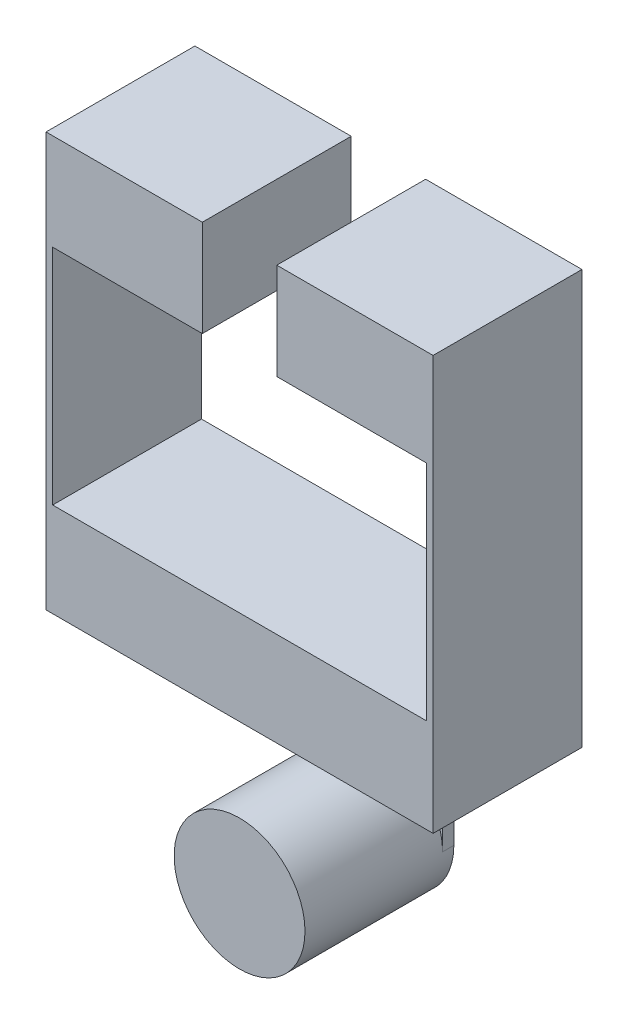
SolidWorks part; units mm, degrees
other "Markup1"
sketch "Sketch7" plane through (31.7043, 97.4003, 0) normal (0.5774, 0.5773, 0.5774) x (0.7071, 0, -0.7071)
ref_plane "Front Plane" through (0, 0, 0) normal (0, 0, 1) x (1, 0, 0)
ref_plane "Top Plane" through (0, 0, 0) normal (0, 1, 0) x (1, 0, 0)
ref_plane "Right Plane" through (0, 0, 0) normal (1, 0, 0) x (0, 0, -1)
sketch "Sketch1" plane through (0, 0, 0) normal (0, 0, 1) x (1, 0, 0)
  circle A0 centre (0, 0) radius 11.1628
  dimension "D1" = 22.3256
extrude "Boss-Extrude1" add sketch "Sketch1" against normal blind 25.4
sketch "Sketch2" plane through (0, 0, -25.4) normal (0, 0, -1) x (-1, 0, 0)
  line L0 (-11.1628, 0) -> (-11.1628, 25.4)
  line L1 (-11.1628, 25.4) -> (11.1628, 25.4)
  line L2 (11.1628, 25.4) -> (11.1628, 0)
  circle A0 centre (0, 0) radius 11.1628 construction
  arc A1 (11.1628, 0) -> (-11.1628, 0) centre (0, 0) ccw
  point P4 (0, 0)
  dimension "D1" = 22.3256
  dimension "D2" = 25.4
extrude "Boss-Extrude2" add sketch "Sketch2" against normal blind 1.9264
ref_plane "Plane1" through (0, 25.4, 0) normal (0, 1, 0) x (1, 0, 0)
sketch "Sketch4" plane through (0, 25.4, 0) normal (0, 1, 0) x (1, 0, 0)
  line L0 (0, 0) -> (0, 55.2267) construction
  line L1 (-33.02, 0) -> (33.02, 0)
  line L2 (-33.02, 0) -> (-33.02, 25.4)
  line L3 (-33.02, 25.4) -> (33.02, 25.4)
  line L4 (33.02, 0) -> (33.02, 25.4)
  point P6 (0, 0)
  dimension "D1" = 25.4
  dimension "D2" = 66.04
extrude "Boss-Extrude3" add sketch "Sketch4" along normal blind 16.0644
sketch "Sketch5" plane through (0, 41.4644, 0) normal (0, 1, 0) x (1, 0, 0)
  line L0 (-33.02, 0) -> (33.02, 0) construction
  line L1 (-33.02, 25.4) -> (-31.8904, 25.4)
  line L2 (-33.02, 25.4) -> (-33.02, 0)
  line L3 (-33.02, 0) -> (-31.8904, 0)
  line L4 (-31.8904, 25.4) -> (-31.8904, 0)
  line L6 (33.02, 25.4) -> (31.8904, 25.4)
  line L7 (33.02, 25.4) -> (33.02, 0)
  line L8 (33.02, 0) -> (31.8904, 0)
  line L9 (31.8904, 25.4) -> (31.8904, 0)
  dimension "D1" = 1.1296
  dimension "D2" = 1.1296
extrude "Boss-Extrude4" add sketch "Sketch5" along normal blind 38.1
sketch "Sketch6" plane through (0, 79.5644, 0) normal (0, 1, 0) x (1, 0, 0)
  line L0 (31.8904, 25.4) -> (-31.8904, 25.4) construction
  line L1 (33.02, 0) -> (6.35, 0)
  line L2 (33.02, 0) -> (33.02, 25.4)
  line L3 (33.02, 25.4) -> (6.35, 25.4)
  line L4 (6.35, 0) -> (6.35, 25.4)
  line L5 (0, 0) -> (0, 25.4) construction
  line L6 (-6.35, 0) -> (-6.35, 25.4)
  line L7 (-33.02, 25.4) -> (-6.35, 25.4)
  line L8 (-33.02, 0) -> (-33.02, 25.4)
  line L9 (-33.02, 0) -> (-6.35, 0)
  dimension "D1" = 26.67
extrude "Boss-Extrude5" add sketch "Sketch6" along normal blind 16.4611
equation "\"F\"= 600"
equation "\"E\"= 29000000"
equation "\"Sy\" = 36000"
equation "\"Tallow\"= 9000"
equation "\"La\"= 1in"
equation "\"SF\" = 4"
equation "\"Z\" =  ( \"SF\" *  ( 2 * \"F\" )  * \"La\" )  /  ( 2 * \"Sy\" ) "
equation "\"Ra\"= ( ( \"Z\" / pi ) * 4 ) ^ ( 1 / 3 )"
equation "\"Bw\"= .879in"
equation "\"Ba\"= ( \"SF\" * \"F\" ) / ( \"Sy\" )"
equation "\"Tb\" = \"Ba\" / \"Bw\""
equation "\"Cw\"=2.6"
equation "\"Ct\"= 1"
equation "\"Ca\"= ( \"SF\" * ( 2 * \"F\" ) ) / \"Sy\""
equation "\"Ch\"= ( \"Z\" * 6 ) ^ ( 1 / 2 )"
equation "\"Da\"= ( \"F\" * \"SF\" ) / ( \"Sy\" )"
equation "\"Dh\"= 1.499"
equation "\"Dw\"= \"Da\" / \"Dh\""
equation "\"Ea\"= ( \"F\" * \"SF\" ) / ( \"Sy\" )"
equation "\"Ew\"=1.05"
equation "\"Ad\"= \"Ra\" * 2"
equation "\"D1@Sketch1\"=\"Ad\""
equation "\"D1@Boss-Extrude1\"=\"La\""
equation "\"D1@Boss-Extrude2\"=\"Tb\""
equation "\"D1@Sketch2\"=\"Ad\""
equation "\"D2@Sketch4\"=\"Cw\""
equation "\"D1@Boss-Extrude3\"=\"Ch\""
equation "\"D1@Sketch5\"=\"Dw\""
equation "\"D2@Sketch5\"=\"Dw\""
equation "\"D1@Sketch6\"=\"Ew\""
equation "\"D1@Boss-Extrude5\"=\"Eh\""
equation "\"Ehtop\" = ( 6 * \"F\" * \"Ew\" * \"SF\" )"
equation "\"Ehbottom\"= ( 1 * \"Sy\" )"
equation "\"Eh\"= ( \"Ehtop\" / \"Ehbottom\" ) ^ ( 1 / 2 )"
